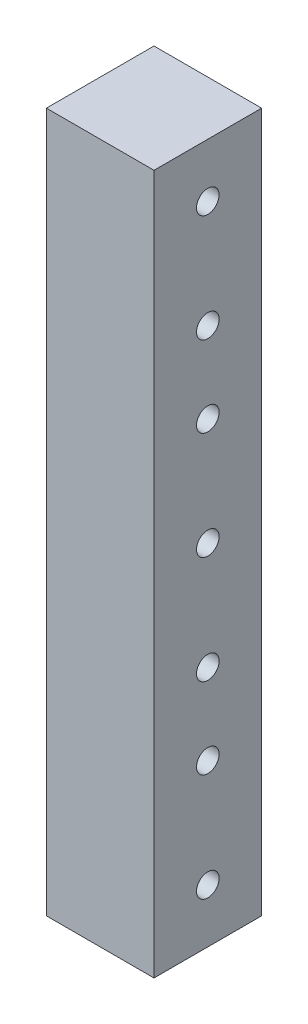
SolidWorks part; units mm, degrees
ref_plane "前视基准面" through (0, 0, 0) normal (0, 0, 1) x (1, 0, 0)
ref_plane "上视基准面" through (0, 0, 0) normal (0, 1, 0) x (1, 0, 0)
ref_plane "右视基准面" through (0, 0, 0) normal (1, 0, 0) x (0, 0, -1)
sketch "草图1" plane through (0, 0, 0) normal (0, 1, 0) x (1, 0, 0)
  line L1 (-10, 10) -> (10, 10)
  line L2 (-10, 10) -> (-10, -10)
  line L3 (-10, -10) -> (10, -10)
  line L4 (10, 10) -> (10, -10)
  line L5 (-10, 10) -> (10, -10) construction
  line L6 (-10, -10) -> (10, 10) construction
  point P0 (0, 0)
  dimension "D1" = 20
  dimension "D2" = 20
extrude "凸台-拉伸1" add sketch "草图1" along normal blind 130
sketch "草图2" plane through (10, 0, 0) normal (1, 0, 0) x (0, 0, -1)
  line L0 (10, 65) -> (-10, 65) construction
  line L1 (10, 130) -> (10, 0) construction
  line L2 (-10, 130) -> (-10, 0) construction
  line L3 (-10, 0) -> (10, 0) construction
  circle A0 centre (0, 45) radius 2.1
  circle A1 centre (0, 65) radius 2.1
  circle A2 centre (0, 85) radius 2.1
  circle A3 centre (0, 10) radius 2.1
  circle A4 centre (0, 30) radius 2.1
  circle A5 centre (0, 100) radius 2.1
  circle A6 centre (0, 120) radius 2.1
  dimension "D1" = 20
  dimension "D3" = 4.2
  dimension "D6" = 4.2
  dimension "D2" = 10
  dimension "D5" = 20
  dimension "D7" = 10
  dimension "D8" = 10
  dimension "D10" = 20
  dimension "D4" = 3
  dimension "D9" = 2
extrude "切除-拉伸1" cut sketch "草图2" against normal through all
